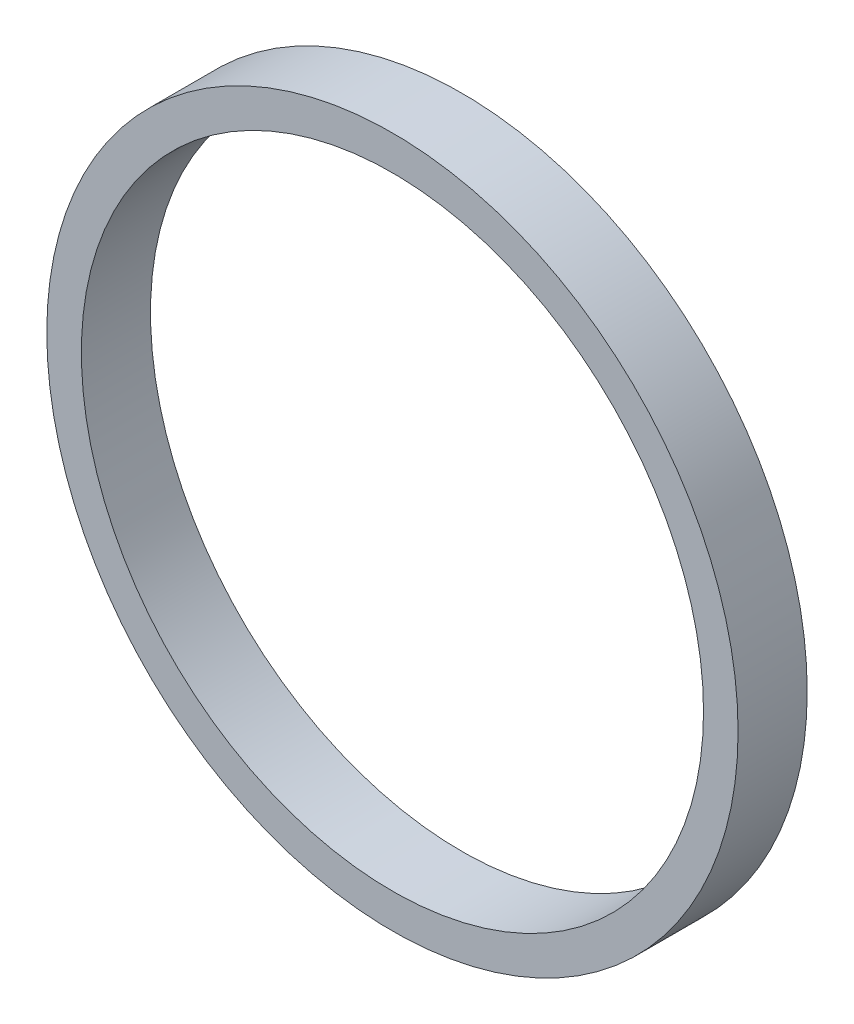
SolidWorks part; units mm, degrees
ref_plane "Front Plane" through (0, 0, 0) normal (0, 0, 1) x (1, 0, 0)
ref_plane "Top Plane" through (0, 0, 0) normal (0, 1, 0) x (1, 0, 0)
ref_plane "Right Plane" through (0, 0, 0) normal (1, 0, 0) x (0, 0, -1)
sketch "Sketch1" plane through (0, 0, 0) normal (0, 0, 1) x (1, 0, 0)
  circle A0 centre (0, 0) radius 50
  circle A1 centre (0, 0) radius 45
  dimension "D1" = 100
  dimension "D2" = 5
extrude "Boss-Extrude1" add sketch "Sketch1" along normal blind 10
